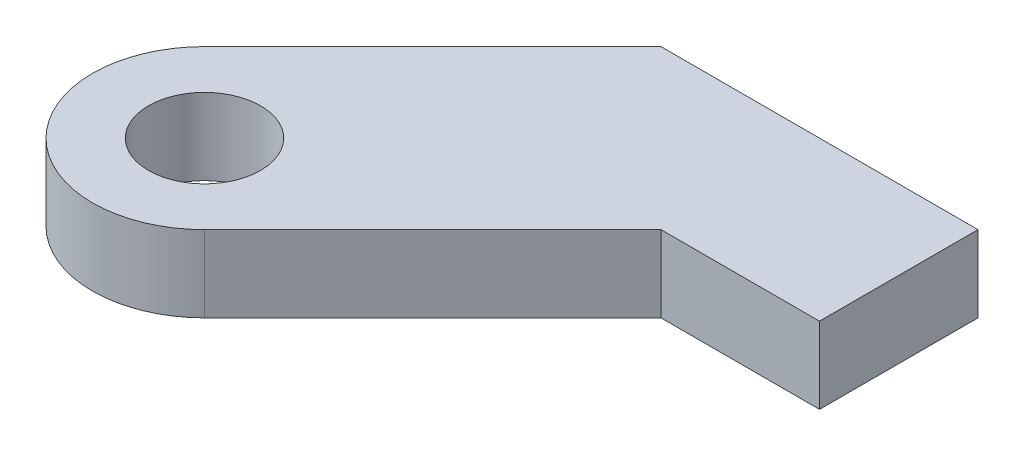
SolidWorks part; units mm, degrees
material "Zoltek Panex 33"
ref_plane "前视基准面" through (0, 0, 0) normal (0, 0, 1) x (1, 0, 0)
ref_plane "上视基准面" through (0, 0, 0) normal (0, 1, 0) x (1, 0, 0)
ref_plane "右视基准面" through (0, 0, 0) normal (1, 0, 0) x (0, 0, -1)
sketch "草图2" plane through (0, 0, 0) normal (0, 1, 0) x (1, 0, 0)
  line L4 (0, 0) -> (2.175, 0) construction
  line L5 (0, 0) -> (0, 2.175) construction
  line L6 (0, 2.175) -> (2.175, 0) construction
  line L7 (0, 0) -> (1.0875, 1.0875) construction
  line L8 (1.0875, 1.0875) -> (1.538, 1.538) construction
  line L9 (1.538, 1.538) -> (4.6492, 1.538)
  line L11 (4.6492, 1.538) -> (4.6492, -1.5733)
  line L12 (1.538, -1.5733) -> (4.6492, -1.5733)
  line L13 (0, 0) -> (-4.4972, -4.4972) construction
  line L14 (1.538, -1.5733) -> (-2.9416, -6.0528)
  line L15 (-1.5733, 1.538) -> (-6.0528, -2.9416)
  line L16 (1.538, 1.538) -> (-1.5733, 1.538)
  arc A5 (-6.0528, -2.9416) -> (-2.9416, -6.0528) centre (-4.4972, -4.4972) ccw
  circle A6 centre (-4.4972, -4.4972) radius 1.1
  point P8 (-4.8943, -4.8943)
  dimension "D1" = 2.2
  dimension "D2" = 6.36
  dimension "D3" = 2.2
  dimension "D4" = 4.4
extrude "凸台-拉伸1" add sketch "草图2" along normal blind 1.5
